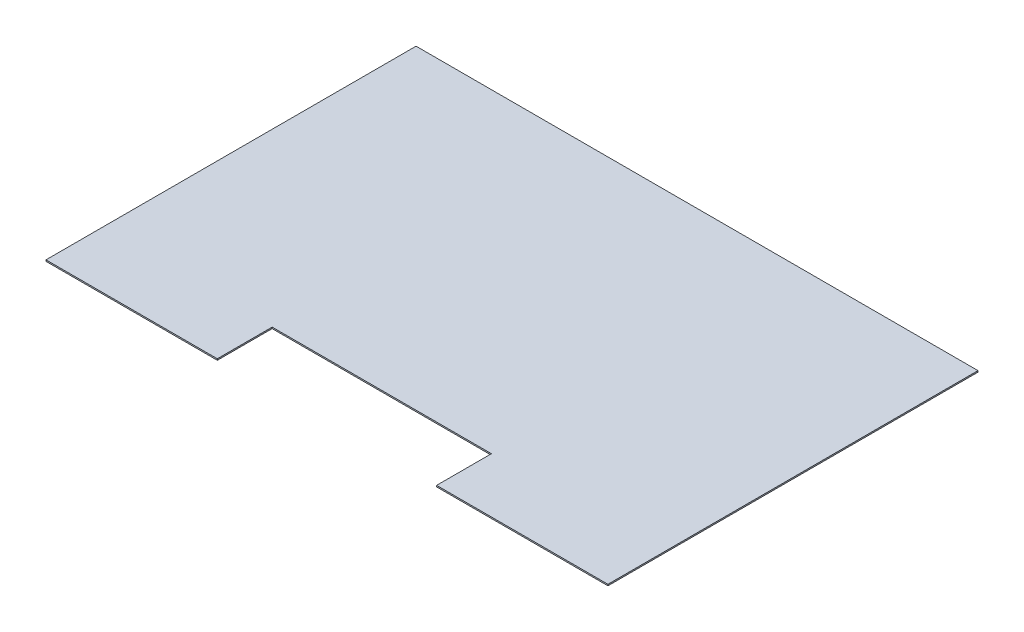
SolidWorks part; units mm, degrees
ref_plane "Front Plane" through (0, 0, 0) normal (0, 0, 1) x (1, 0, 0)
ref_plane "Top Plane" through (0, 0, 0) normal (0, 1, 0) x (1, 0, 0)
ref_plane "Right Plane" through (0, 0, 0) normal (1, 0, 0) x (0, 0, -1)
sketch "Szkic1" plane through (0, 0, 0) normal (0, 1, 0) x (1, 0, 0)
  line L0 (-205, -135) -> (205, 135) construction
  line L1 (-205, 135) -> (205, 135)
  line L2 (-205, 135) -> (-205, -135)
  line L3 (-205, -135) -> (205, -135)
  line L4 (205, 135) -> (205, -135)
  line L5 (0, -95) -> (0, 135) construction
  line L6 (-80, -135) -> (80, -135)
  line L7 (-80, -135) -> (-80, -95)
  line L8 (-80, -95) -> (80, -95)
  line L9 (80, -135) -> (80, -95)
  point P11 (0, 0)
  point P12 (0, 135)
  dimension "D1" = 410
  dimension "D2" = 270
  dimension "D3" = 230
  dimension "D4" = 160
extrude "Dodanie-wyciągnięcie1" add sketch "Szkic1" along normal blind 1 contours L9 L3 L4 L1 L2 L7 L8
